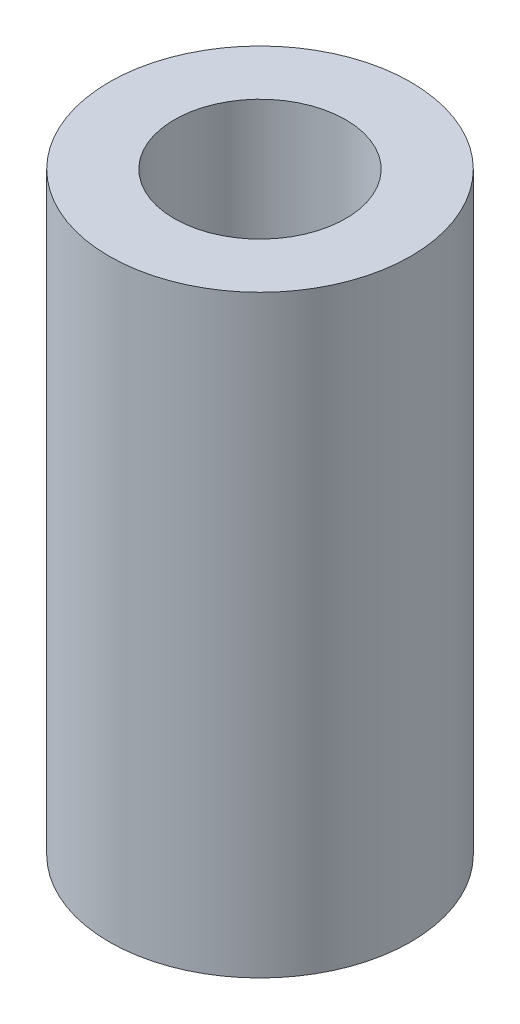
SolidWorks part; units mm, degrees
ref_plane "Front Plane" through (0, 0, 0) normal (0, 0, 1) x (1, 0, 0)
ref_plane "Top Plane" through (0, 0, 0) normal (0, 1, 0) x (1, 0, 0)
ref_plane "Right Plane" through (0, 0, 0) normal (1, 0, 0) x (0, 0, -1)
sketch "Sketch2" plane through (0, 0, 0) normal (0, 1, 0) x (1, 0, 0)
  circle A0 centre (0, 0) radius 2.794
  circle A1 centre (0, 0) radius 1.5875
  dimension "D1" = 5.588
  dimension "D2" = 3.175
extrude "Boss-Extrude1" add sketch "Sketch2" along normal blind 11
fillet "Fillet1" radius 0.5953 1 edges at (0, 0, 1.5875)
